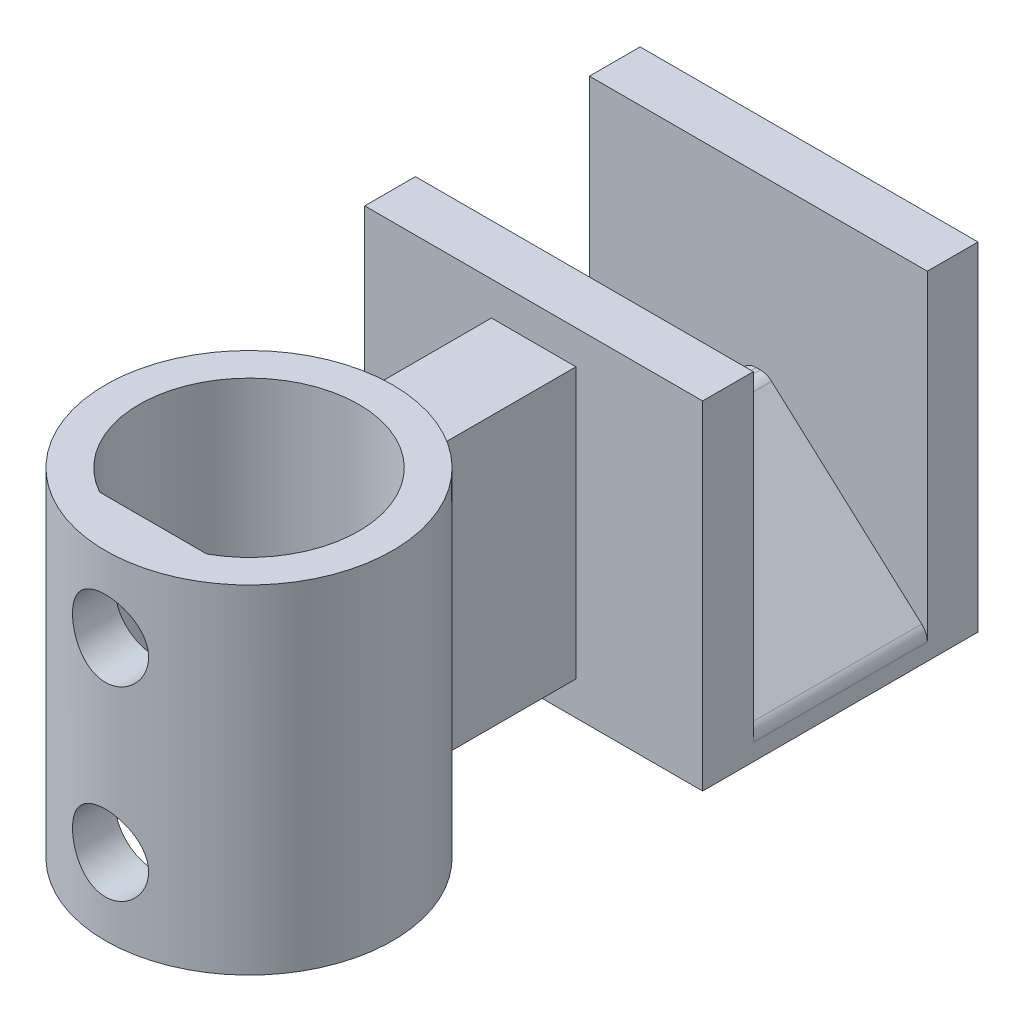
SolidWorks part; units mm, degrees
material "ABS"
ref_plane "Front Plane" through (0, 0, 0) normal (0, 0, 1) x (1, 0, 0)
ref_plane "Top Plane" through (0, 0, 0) normal (0, 1, 0) x (1, 0, 0)
ref_plane "Right Plane" through (0, 0, 0) normal (1, 0, 0) x (0, 0, -1)
sketch "Sketch2" plane through (0, 0, 0) normal (0, 0, 1) x (1, 0, 0)
  line L1 (-10, -5) -> (10, -5)
  line L2 (-10, -5) -> (-10, 5)
  line L3 (-10, 5) -> (10, 5)
  line L4 (10, -5) -> (10, 5)
  line L5 (-10, -5) -> (10, 5) construction
  line L6 (-10, 5) -> (10, -5) construction
  point P0 (0, 0)
  dimension "D1" = 10
  dimension "D2" = 20
extrude "Boss-Extrude1" add sketch "Sketch2" along normal mid plane 10.3
chamfer "Chamfer1" distance 9.5 angle 42 2 edges at (10, 5, 0) (-10, 5, 0)
fillet "Fillet3" radius 1 4 edges at (-10, -3.5538, 0) (10, -3.5538, 0) (0.5, 5, 0) (-0.5, 5, 0)
sketch "Sketch3" plane through (0, 0, 5.15) normal (0, 0, 1) x (1, 0, 0)
  line L0 (-10, -5) -> (10, -5) construction
  line L1 (-10, 15) -> (10, 15)
  line L2 (-10, 15) -> (-10, -5)
  line L3 (-10, -5) -> (10, -5)
  line L4 (10, 15) -> (10, -5)
  line L5 (-10, 15) -> (10, -5) construction
  line L6 (-10, -5) -> (10, 15) construction
  point P0 (0, 5)
  dimension "D1" = 20
  dimension "D2" = 20
extrude "Boss-Extrude2" add sketch "Sketch3" along normal blind 3
mirror "Mirror1" about plane through (0, 0, 0) normal (0, 0, 1) of "Boss-Extrude2"
sketch "Sketch6" plane through (0, 0, 0) normal (0, 1, 0) x (1, 0, 0)
  line L0 (3.175, -30.6718) -> (-3.175, -30.6718)
  arc A0 (3.175, -30.6718) -> (-3.175, -30.6718) centre (0, -25) ccw
  circle A1 centre (0, -25) radius 8.5
  dimension "D1" = 13
  dimension "D2" = 2
  dimension "D3" = 25
  dimension "D4" = 6.35
extrude "Boss-Extrude3" add sketch "Sketch6" along normal up to surface and the other way up to surface separate body up to face at (0, 15, 6.65) other way up to face at (0, -5, 0)
sketch "Sketch5" plane through (0, 0, 8.15) normal (0, 0, 1) x (1, 0, 0)
  line L0 (-10, -5) -> (10, -5) construction
  line L1 (-2.5, 13) -> (2.5, 13)
  line L2 (-2.5, 13) -> (-2.5, -3)
  line L3 (-2.5, -3) -> (2.5, -3)
  line L4 (2.5, 13) -> (2.5, -3)
  line L5 (-2.5, 13) -> (2.5, -3) construction
  line L6 (-2.5, -3) -> (2.5, 13) construction
  line L7 (10, 15) -> (-10, 15) construction
  point P0 (0, 5)
  dimension "D1" = 2
  dimension "D2" = 2
  dimension "D3" = 5
extrude "Boss-Extrude4" add sketch "Sketch5" along normal up to surface (8.726 mm away)
ref_plane "Plane1" through (0, 0, 20) normal (0, 0, 1) x (1, 0, 0)
sketch "Sketch7" plane through (0, 0, 20) normal (0, 0, 1) x (1, 0, 0)
  line L0 (-8.5, -5) -> (8.5, -5) construction
  line L1 (6.5, 15) -> (-6.5, 15) construction
  circle A0 centre (0, 10.5) radius 2.25
  circle A1 centre (0, -0.5) radius 2.25
  dimension "D1" = 4.5
  dimension "D2" = 4.5
  dimension "D3" = 4.5
  dimension "D4" = 4.5
extrude "Cut-Extrude1" cut sketch "Sketch7" along normal up to surface (13.1968 mm away)
